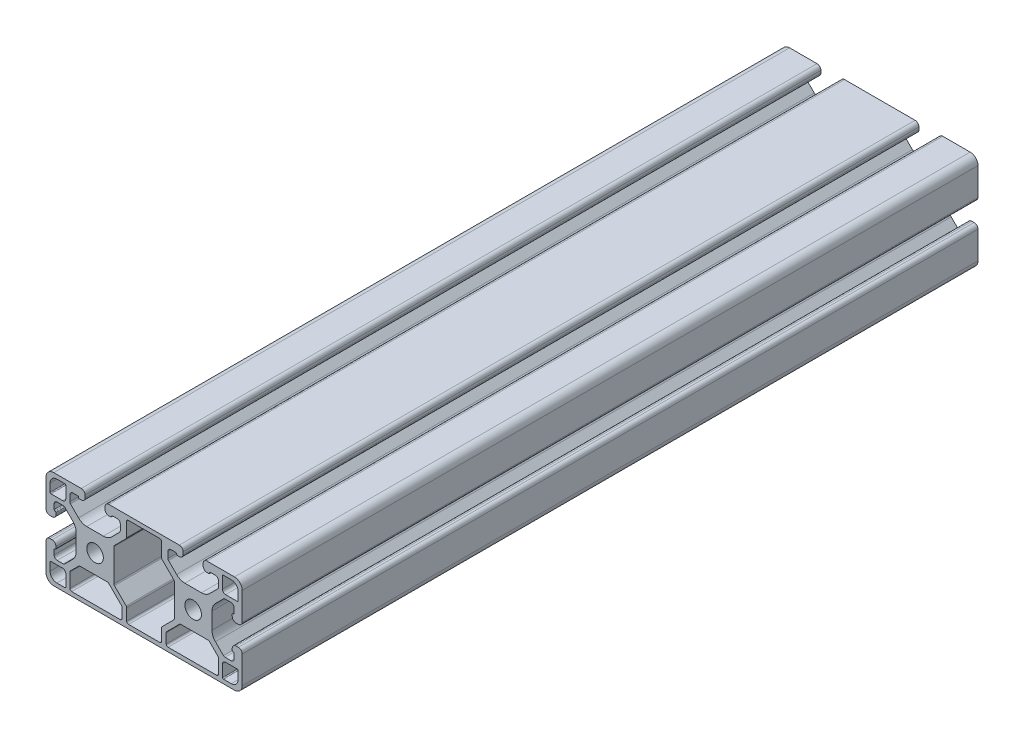
SolidWorks part; units mm, degrees
material "6105-T5 Aluminum"
ref_plane "Front Plane" through (0, 0, 0) normal (0, 0, 1) x (1, 0, 0)
ref_plane "Top Plane" through (0, 0, 0) normal (0, 1, 0) x (1, 0, 0)
ref_plane "Right Plane" through (0, 0, 0) normal (1, 0, 0) x (0, 0, -1)
sketch "Sketch1" plane through (0, 0, 0) normal (0, 0, 1) x (1, 0, 0)
  line L0 (-10.9841, -17.5873) -> (-10.9841, -13.6343)
  line L1 (-10.761, -13.0955) -> (-5.5711, -7.9057)
  line L2 (-5.0324, -7.6825) -> (6.1099, -7.6825)
  line L3 (6.6486, -7.9057) -> (10.0626, -11.3196)
  line L4 (10.2857, -11.8584) -> (10.2857, -17.5873)
  line L5 (9.5238, -18.3492) -> (-10.2222, -18.3492)
  line L6 (-46.1099, -7.6825) -> (-34.9676, -7.6825)
  line L7 (-34.4289, -7.9057) -> (-29.239, -13.0955)
  line L8 (-29.0159, -13.6343) -> (-29.0159, -17.5873)
  line L9 (-29.7778, -18.3492) -> (-49.5238, -18.3492)
  line L10 (-50.2857, -17.5873) -> (-50.2857, -11.8584)
  line L11 (-50.0626, -11.3196) -> (-46.6486, -7.9057)
  line L12 (-13.6508, -18.3492) -> (-26.3492, -18.3492)
  line L13 (-27.1111, -17.5873) -> (-27.1111, -12.8453)
  line L14 (-27.3343, -12.3066) -> (-32.0943, -7.5465)
  line L15 (-32.3175, -7.0078) -> (-32.3175, 6.1099)
  line L16 (-32.0943, 6.6486) -> (-27.3978, 11.3452)
  line L17 (-27.1746, 11.8839) -> (-27.1746, 17.5873)
  line L18 (-26.4127, 18.3492) -> (-13.5873, 18.3492)
  line L19 (-12.8254, 17.5873) -> (-12.8254, 11.8839)
  line L20 (-12.6022, 11.3452) -> (-7.9057, 6.6486)
  line L21 (-7.6825, 6.1099) -> (-7.6825, -7.0078)
  line L22 (-7.9057, -7.5465) -> (-12.6657, -12.3066)
  line L23 (-12.8889, -12.8453) -> (-12.8889, -17.5873)
  line L24 (-52.3165, -18.3492) -> (-55.5555, -18.3492)
  line L25 (-58.3495, -15.5552) -> (-58.3495, -12.3165)
  line L26 (-57.9695, -11.9365) -> (-53.2063, -11.9365)
  line L27 (-51.9365, -13.2063) -> (-51.9365, -17.9693)
  line L28 (-55.5555, 18.3492) -> (-52.3165, 18.3492)
  line L29 (-51.9365, 17.9693) -> (-51.9365, 13.2063)
  line L30 (-53.2063, 11.9365) -> (-57.9695, 11.9365)
  line L31 (-58.3495, 12.3165) -> (-58.3495, 15.5552)
  line L32 (15.5555, -18.3492) -> (12.3165, -18.3492)
  line L33 (11.9365, -17.9693) -> (11.9365, -13.2063)
  line L34 (13.2063, -11.9365) -> (17.9695, -11.9365)
  line L35 (18.3495, -12.3165) -> (18.3495, -15.5552)
  line L36 (12.3165, 18.3492) -> (15.5555, 18.3492)
  line L37 (18.3495, 15.5552) -> (18.3495, 12.3165)
  line L38 (17.9695, 11.9365) -> (13.2063, 11.9365)
  line L39 (11.9365, 13.2063) -> (11.9365, 17.9693)
  line L40 (-5.6381, 20) -> (-34.3619, 20)
  line L41 (-35.9365, 18.4254) -> (-35.9365, 17.5111)
  line L42 (-34.3619, 15.9365) -> (-33.6554, 15.9365)
  line L43 (-33.2757, 16.3032) -> (-33.2747, 16.3317)
  line L44 (-32.895, 16.6984) -> (-30.9841, 16.6984)
  line L45 (-29.7143, 15.4286) -> (-29.7143, 12.9885)
  line L46 (-29.9746, 12.3599) -> (-33.261, 9.0736)
  line L47 (-36.6192, 7.6825) -> (-43.3808, 7.6825)
  line L48 (-46.739, 9.0736) -> (-50.0254, 12.3599)
  line L49 (-50.2857, 12.9885) -> (-50.2857, 15.4286)
  line L50 (-49.0159, 16.6984) -> (-46.7381, 16.6984)
  line L51 (-46.7381, 16.6984) -> (-46.7115, 15.9365)
  line L52 (-46.7115, 15.9365) -> (-45.6381, 15.9365)
  line L53 (-44.0635, 17.5111) -> (-44.0635, 18.4254)
  line L54 (-45.6381, 20) -> (-56.8254, 20)
  line L55 (-60, 16.8252) -> (-59.9994, 5.6381)
  line L56 (-58.4248, 4.0635) -> (-57.5105, 4.0635)
  line L57 (-55.9359, 5.6381) -> (-55.9359, 6.3092)
  line L58 (-56.3026, 6.689) -> (-56.3311, 6.69)
  line L59 (-56.6978, 7.0697) -> (-56.6978, 9.0159)
  line L60 (-55.428, 10.2857) -> (-52.9885, 10.2857)
  line L61 (-52.3599, 10.0254) -> (-49.0736, 6.739)
  line L62 (-47.6825, 3.3808) -> (-47.6825, -3.3808)
  line L63 (-49.0736, -6.739) -> (-52.3599, -10.0254)
  line L64 (-52.9885, -10.2857) -> (-55.4286, -10.2857)
  line L65 (-56.6984, -9.0159) -> (-56.6984, -7.105)
  line L66 (-55.9365, -6.3451) -> (-55.9365, -5.6381)
  line L67 (-57.5111, -4.0635) -> (-58.4254, -4.0635)
  line L68 (-60, -5.6381) -> (-60, -16.8254)
  line L69 (-56.8254, -20) -> (16.8254, -20)
  line L70 (20, -16.8254) -> (20, -5.6381)
  line L71 (18.4254, -4.0635) -> (17.5111, -4.0635)
  line L72 (15.9365, -5.6381) -> (15.9365, -6.3446)
  line L73 (16.3032, -6.7243) -> (16.3317, -6.7253)
  line L74 (16.6984, -7.105) -> (16.6984, -9.0159)
  line L75 (15.4286, -10.2857) -> (12.9885, -10.2857)
  line L76 (12.3599, -10.0254) -> (9.0736, -6.739)
  line L77 (7.6825, -3.3808) -> (7.6825, 3.3808)
  line L78 (9.0736, 6.739) -> (12.3599, 10.0254)
  line L79 (12.9885, 10.2857) -> (15.4286, 10.2857)
  line L80 (16.6984, 9.0159) -> (16.6984, 7.105)
  line L81 (16.3317, 6.7253) -> (16.3032, 6.7243)
  line L82 (15.9365, 6.3446) -> (15.9365, 5.5746)
  line L83 (17.5022, 4.0635) -> (18.4165, 4.0635)
  line L84 (20, 5.5746) -> (20, 16.8254)
  line L85 (16.8254, 20) -> (5.6381, 20)
  line L86 (4.0635, 18.4254) -> (4.0635, 17.5111)
  line L87 (5.6381, 15.9365) -> (6.3446, 15.9365)
  line L88 (6.7243, 16.3032) -> (6.7253, 16.3317)
  line L89 (7.105, 16.6984) -> (9.0159, 16.6984)
  line L90 (10.2857, 15.4286) -> (10.2857, 12.9885)
  line L91 (10.0254, 12.3599) -> (6.739, 9.0736)
  line L92 (3.3808, 7.6825) -> (-3.3808, 7.6825)
  line L93 (-6.739, 9.0736) -> (-10.0254, 12.3599)
  line L94 (-10.2857, 12.9885) -> (-10.2857, 15.4346)
  line L95 (-9.0125, 16.7044) -> (-7.104, 16.6994)
  line L96 (-6.7253, 16.3327) -> (-6.7243, 16.3032)
  line L97 (-6.3446, 15.9365) -> (-5.6381, 15.9365)
  line L98 (-4.0635, 17.5111) -> (-4.0635, 18.4254)
  arc A0 (-10.9841, -17.5873) -> (-10.2222, -18.3492) centre (-10.2222, -17.5873) ccw
  arc A1 (-10.761, -13.0955) -> (-10.9841, -13.6343) centre (-10.2222, -13.6343) ccw
  arc A2 (-5.0324, -7.6825) -> (-5.5711, -7.9057) centre (-5.0324, -8.4444) ccw
  arc A3 (6.6486, -7.9057) -> (6.1099, -7.6825) centre (6.1099, -8.4444) ccw
  arc A4 (10.2857, -11.8584) -> (10.0626, -11.3196) centre (9.5238, -11.8584) ccw
  arc A5 (9.5238, -18.3492) -> (10.2857, -17.5873) centre (9.5238, -17.5873) ccw
  arc A6 (-46.1099, -7.6825) -> (-46.6486, -7.9057) centre (-46.1099, -8.4444) ccw
  arc A7 (-34.4289, -7.9057) -> (-34.9676, -7.6825) centre (-34.9676, -8.4444) ccw
  arc A8 (-29.0159, -13.6343) -> (-29.239, -13.0955) centre (-29.7778, -13.6343) ccw
  arc A9 (-29.7778, -18.3492) -> (-29.0159, -17.5873) centre (-29.7778, -17.5873) ccw
  arc A10 (-50.2857, -17.5873) -> (-49.5238, -18.3492) centre (-49.5238, -17.5873) ccw
  arc A11 (-50.0626, -11.3196) -> (-50.2857, -11.8584) centre (-49.5238, -11.8584) ccw
  arc A12 (-27.1111, -17.5873) -> (-26.3492, -18.3492) centre (-26.3492, -17.5873) ccw
  arc A13 (-27.1111, -12.8453) -> (-27.3343, -12.3066) centre (-27.873, -12.8453) ccw
  arc A14 (-32.3175, -7.0078) -> (-32.0943, -7.5465) centre (-31.5556, -7.0078) ccw
  arc A15 (-32.0943, 6.6486) -> (-32.3175, 6.1099) centre (-31.5556, 6.1099) ccw
  arc A16 (-27.3978, 11.3452) -> (-27.1746, 11.8839) centre (-27.9365, 11.8839) ccw
  arc A17 (-26.4127, 18.3492) -> (-27.1746, 17.5873) centre (-26.4127, 17.5873) ccw
  arc A18 (-12.8254, 17.5873) -> (-13.5873, 18.3492) centre (-13.5873, 17.5873) ccw
  arc A19 (-12.8254, 11.8839) -> (-12.6022, 11.3452) centre (-12.0635, 11.8839) ccw
  arc A20 (-7.6825, 6.1099) -> (-7.9057, 6.6486) centre (-8.4444, 6.1099) ccw
  arc A21 (-7.9057, -7.5465) -> (-7.6825, -7.0078) centre (-8.4444, -7.0078) ccw
  arc A22 (-12.6657, -12.3066) -> (-12.8889, -12.8453) centre (-12.127, -12.8453) ccw
  arc A23 (-13.6508, -18.3492) -> (-12.8889, -17.5873) centre (-13.6508, -17.5873) ccw
  arc A24 (-58.3495, -15.5552) -> (-55.5555, -18.3492) centre (-55.5555, -15.5552) ccw
  arc A25 (-57.9695, -11.9365) -> (-58.3495, -12.3165) centre (-57.9695, -12.3165) ccw
  arc A26 (-51.9365, -13.2063) -> (-53.2063, -11.9365) centre (-53.2063, -13.2063) ccw
  arc A27 (-52.3165, -18.3492) -> (-51.9365, -17.9693) centre (-52.3165, -17.9693) ccw
  circle A28 centre (0, 0) radius 3.3778
  circle A29 centre (-40, 0) radius 3.3778
  arc A30 (-51.9365, 17.9693) -> (-52.3165, 18.3492) centre (-52.3165, 17.9693) ccw
  arc A31 (-53.2063, 11.9365) -> (-51.9365, 13.2063) centre (-53.2063, 13.2063) ccw
  arc A32 (-58.3495, 12.3165) -> (-57.9695, 11.9365) centre (-57.9695, 12.3165) ccw
  arc A33 (-55.5555, 18.3492) -> (-58.3495, 15.5552) centre (-55.5555, 15.5552) ccw
  arc A34 (11.9365, -17.9693) -> (12.3165, -18.3492) centre (12.3165, -17.9693) ccw
  arc A35 (13.2063, -11.9365) -> (11.9365, -13.2063) centre (13.2063, -13.2063) ccw
  arc A36 (18.3495, -12.3165) -> (17.9695, -11.9365) centre (17.9695, -12.3165) ccw
  arc A37 (15.5555, -18.3492) -> (18.3495, -15.5552) centre (15.5555, -15.5552) ccw
  arc A38 (18.3495, 15.5552) -> (15.5555, 18.3492) centre (15.5555, 15.5552) ccw
  arc A39 (17.9695, 11.9365) -> (18.3495, 12.3165) centre (17.9695, 12.3165) ccw
  arc A40 (11.9365, 13.2063) -> (13.2063, 11.9365) centre (13.2063, 13.2063) ccw
  arc A41 (12.3165, 18.3492) -> (11.9365, 17.9693) centre (12.3165, 17.9693) ccw
  arc A42 (-4.0635, 18.4254) -> (-5.6381, 20) centre (-5.6381, 18.4254) ccw
  arc A43 (-34.3619, 20) -> (-35.9365, 18.4254) centre (-34.3619, 18.4254) ccw
  arc A44 (-35.9365, 17.5111) -> (-34.3619, 15.9365) centre (-34.3619, 17.5111) ccw
  arc A45 (-33.6554, 15.9365) -> (-33.2757, 16.3032) centre (-33.6554, 16.3165) ccw
  arc A46 (-32.895, 16.6984) -> (-33.2747, 16.3317) centre (-32.895, 16.3185) ccw
  arc A47 (-29.7143, 15.4286) -> (-30.9841, 16.6984) centre (-30.9841, 15.4286) ccw
  arc A48 (-29.9746, 12.3599) -> (-29.7143, 12.9885) centre (-30.6032, 12.9885) ccw
  arc A49 (-36.6192, 7.6825) -> (-33.261, 9.0736) centre (-36.6192, 12.4317) ccw
  arc A50 (-46.739, 9.0736) -> (-43.3808, 7.6825) centre (-43.3808, 12.4317) ccw
  arc A51 (-50.2857, 12.9885) -> (-50.0254, 12.3599) centre (-49.3968, 12.9885) ccw
  arc A52 (-49.0159, 16.6984) -> (-50.2857, 15.4286) centre (-49.0159, 15.4286) ccw
  arc A53 (-45.6381, 15.9365) -> (-44.0635, 17.5111) centre (-45.6381, 17.5111) ccw
  arc A54 (-44.0635, 18.4254) -> (-45.6381, 20) centre (-45.6381, 18.4254) ccw
  arc A55 (-56.8254, 20) -> (-60, 16.8252) centre (-56.8254, 16.8254) ccw
  arc A56 (-59.9994, 5.6381) -> (-58.4248, 4.0635) centre (-58.4248, 5.6381) ccw
  arc A57 (-57.5105, 4.0635) -> (-55.9359, 5.6381) centre (-57.5105, 5.6381) ccw
  arc A58 (-55.9359, 6.3092) -> (-56.3026, 6.689) centre (-56.3158, 6.3092) ccw
  arc A59 (-56.6978, 7.0697) -> (-56.3311, 6.69) centre (-56.3178, 7.0697) ccw
  arc A60 (-55.428, 10.2857) -> (-56.6978, 9.0159) centre (-55.428, 9.0159) ccw
  arc A61 (-52.3599, 10.0254) -> (-52.9885, 10.2857) centre (-52.9885, 9.3968) ccw
  arc A62 (-47.6825, 3.3808) -> (-49.0736, 6.739) centre (-52.4317, 3.3808) ccw
  arc A63 (-49.0736, -6.739) -> (-47.6825, -3.3808) centre (-52.4317, -3.3808) ccw
  arc A64 (-52.9885, -10.2857) -> (-52.3599, -10.0254) centre (-52.9885, -9.3968) ccw
  arc A65 (-56.6984, -9.0159) -> (-55.4286, -10.2857) centre (-55.4286, -9.0159) ccw
  arc A66 (-56.3175, -6.7251) -> (-56.6984, -7.105) centre (-56.3185, -7.105) ccw
  arc A67 (-56.3175, -6.7251) -> (-55.9365, -6.3451) centre (-56.3165, -6.3451) ccw
  arc A68 (-55.9365, -5.6381) -> (-57.5111, -4.0635) centre (-57.5111, -5.6381) ccw
  arc A69 (-58.4254, -4.0635) -> (-60, -5.6381) centre (-58.4254, -5.6381) ccw
  arc A70 (-60, -16.8254) -> (-56.8254, -20) centre (-56.8254, -16.8254) ccw
  arc A71 (16.8254, -20) -> (20, -16.8254) centre (16.8254, -16.8254) ccw
  arc A72 (20, -5.6381) -> (18.4254, -4.0635) centre (18.4254, -5.6381) ccw
  arc A73 (17.5111, -4.0635) -> (15.9365, -5.6381) centre (17.5111, -5.6381) ccw
  arc A74 (15.9365, -6.3446) -> (16.3032, -6.7243) centre (16.3165, -6.3446) ccw
  arc A75 (16.6984, -7.105) -> (16.3317, -6.7253) centre (16.3185, -7.105) ccw
  arc A76 (15.4286, -10.2857) -> (16.6984, -9.0159) centre (15.4286, -9.0159) ccw
  arc A77 (12.3599, -10.0254) -> (12.9885, -10.2857) centre (12.9885, -9.3968) ccw
  arc A78 (7.6825, -3.3808) -> (9.0736, -6.739) centre (12.4317, -3.3808) ccw
  arc A79 (9.0736, 6.739) -> (7.6825, 3.3808) centre (12.4317, 3.3808) ccw
  arc A80 (12.9885, 10.2857) -> (12.3599, 10.0254) centre (12.9885, 9.3968) ccw
  arc A81 (16.6984, 9.0159) -> (15.4286, 10.2857) centre (15.4286, 9.0159) ccw
  arc A82 (16.3317, 6.7253) -> (16.6984, 7.105) centre (16.3185, 7.105) ccw
  arc A83 (16.3032, 6.7243) -> (15.9365, 6.3446) centre (16.3165, 6.3446) ccw
  arc A84 (15.9365, 5.5746) -> (17.5022, 4.0635) centre (17.4965, 5.6242) ccw
  arc A85 (18.4165, 4.0635) -> (20, 5.5746) centre (18.4087, 5.6569) ccw
  arc A86 (20, 16.8254) -> (16.8254, 20) centre (16.8254, 16.8254) ccw
  arc A87 (5.6381, 20) -> (4.0635, 18.4254) centre (5.6381, 18.4254) ccw
  arc A88 (4.0635, 17.5111) -> (5.6381, 15.9365) centre (5.6381, 17.5111) ccw
  arc A89 (6.3446, 15.9365) -> (6.7243, 16.3032) centre (6.3446, 16.3165) ccw
  arc A90 (7.105, 16.6984) -> (6.7253, 16.3317) centre (7.105, 16.3185) ccw
  arc A91 (10.2857, 15.4286) -> (9.0159, 16.6984) centre (9.0159, 15.4286) ccw
  arc A92 (10.0254, 12.3599) -> (10.2857, 12.9885) centre (9.3968, 12.9885) ccw
  arc A93 (3.3808, 7.6825) -> (6.739, 9.0736) centre (3.3808, 12.4317) ccw
  arc A94 (-6.739, 9.0736) -> (-3.3808, 7.6825) centre (-3.3808, 12.4317) ccw
  arc A95 (-10.2857, 12.9885) -> (-10.0254, 12.3599) centre (-9.3968, 12.9885) ccw
  arc A96 (-9.0125, 16.7044) -> (-10.2857, 15.4346) centre (-9.0159, 15.4346) ccw
  arc A97 (-6.7253, 16.3327) -> (-7.104, 16.6994) centre (-7.105, 16.3194) ccw
  arc A98 (-6.7243, 16.3032) -> (-6.3446, 15.9365) centre (-6.3446, 16.3165) ccw
  arc A99 (-5.6381, 15.9365) -> (-4.0635, 17.5111) centre (-5.6381, 17.5111) ccw
extrude "Extrude1" add sketch "Sketch1" against normal blind 300
